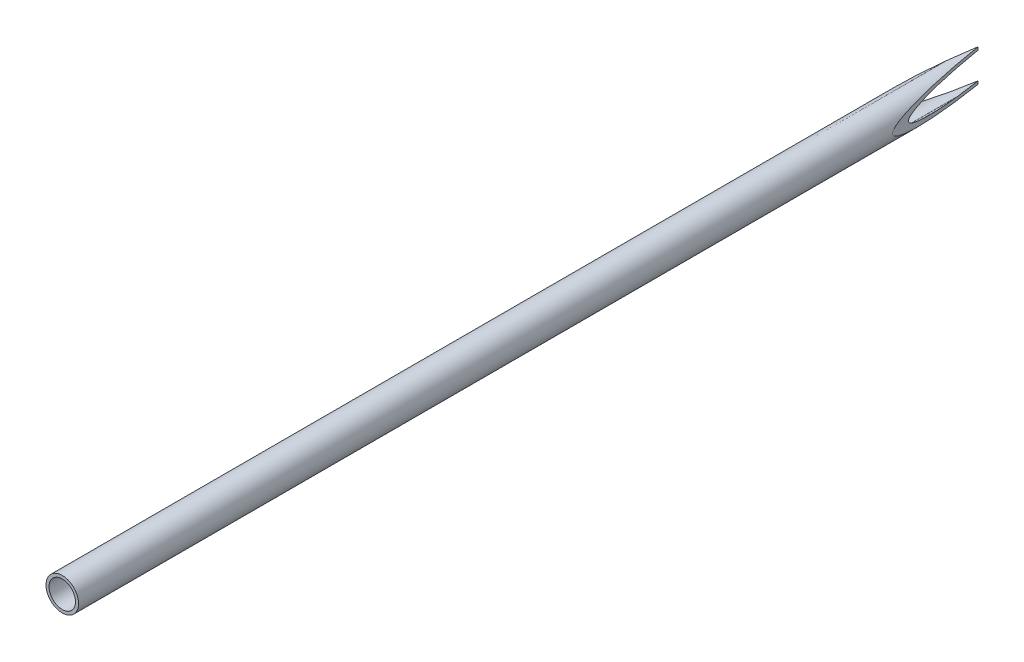
SolidWorks part; units mm, degrees
ref_plane "Plan de face" through (0, 0, 0) normal (0, 0, 1) x (1, 0, 0)
ref_plane "Plan de dessus" through (0, 0, 0) normal (0, 1, 0) x (1, 0, 0)
ref_plane "Plan de droite" through (0, 0, 0) normal (1, 0, 0) x (0, 0, -1)
sketch "Esquisse1" plane through (0, 0, 0) normal (0, 0, 1) x (1, 0, 0)
  circle A0 centre (0, 0) radius 16
  circle A1 centre (0, 0) radius 13
  dimension "D1" = 32
  dimension "D2" = 26
extrude "Boss.-Extru.1" add sketch "Esquisse1" along normal blind 900
sketch "Esquisse2" plane through (0, 0, 0) normal (0, 1, 0) x (1, 0, 0)
  line L0 (0, 0) -> (16, -100)
  line L1 (16, -900) -> (16, 0) construction
  line L2 (16, -100) -> (16, 0)
  line L3 (16, 0) -> (0, 0)
  dimension "D1" = 100
extrude "Enlèv. mat.-Extru.1" cut sketch "Esquisse2" against normal through all both and the other way through all
sketch "Esquisse3" plane through (0, 0, 0) normal (0, 1, 0) x (1, 0, 0)
  line L0 (0, 0) -> (-16, -100)
  line L1 (-16, 0) -> (-16, -900) construction
  line L2 (-16, -100) -> (-16, 0)
  line L3 (-16, 0) -> (0, 0)
  dimension "D1" = 100
extrude "Enlèv. mat.-Extru.2" cut sketch "Esquisse3" against normal through all both and the other way through all
